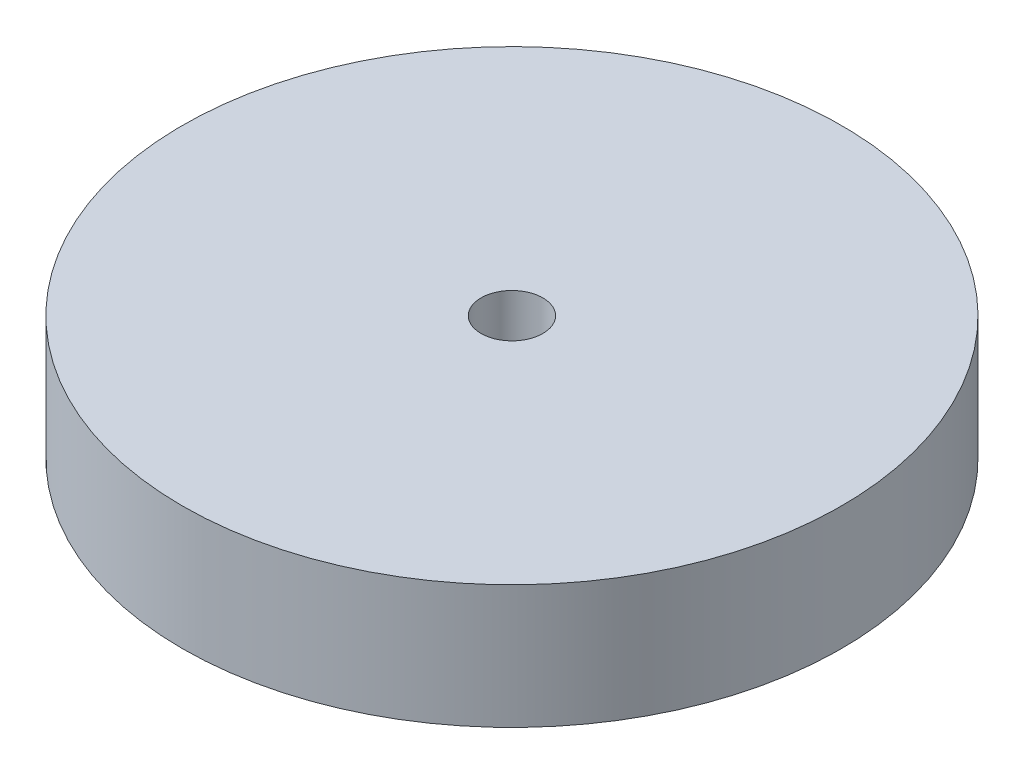
SolidWorks part; units mm, degrees
material "Д16Т ГОСТ 4784-97"
ref_plane "Front Plane" through (0, 0, 0) normal (0, 0, 1) x (1, 0, 0)
ref_plane "Top Plane" through (0, 0, 0) normal (0, 1, 0) x (1, 0, 0)
ref_plane "Right Plane" through (0, 0, 0) normal (1, 0, 0) x (0, 0, -1)
sketch "Sketch1" plane through (0, 0, 0) normal (0, 1, 0) x (1, 0, 0)
  circle A0 centre (0, 0) radius 160
  circle A1 centre (0, 0) radius 15
  dimension "D1" = 320
  dimension "D2" = 30
extrude "Boss-Extrude1" add sketch "Sketch1" along normal mid plane 60
